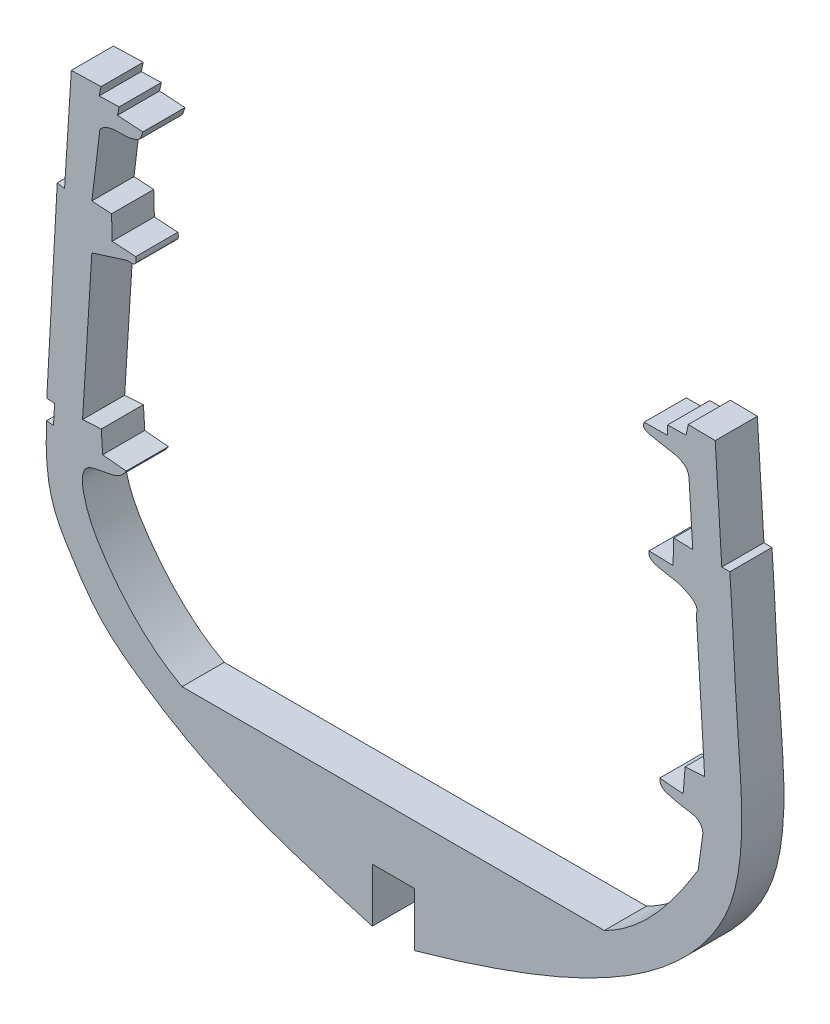
SolidWorks part; units mm, degrees
ref_plane "前视基准面" through (0, 0, 0) normal (0, 0, 1) x (1, 0, 0)
ref_plane "上视基准面" through (0, 0, 0) normal (0, 1, 0) x (1, 0, 0)
ref_plane "右视基准面" through (0, 0, 0) normal (1, 0, 0) x (0, 0, -1)
other "Configuration Table"
sketch "草图1" plane through (0, 0, 0) normal (0, 0, 1) x (1, 0, 0)
  line L0 (376.5, 617) -> (1882.5, 617) construction
  line L1 (1124.0285, 520.4301) -> (1204.1749, 520.4301)
  line L2 (1160.129, 499.1136) -> (1160.1399, 509.3173)
  line L3 (1160.1399, 509.3173) -> (1168.1384, 509.3088)
  line L4 (1168.1384, 509.3088) -> (1168.1276, 499.1038)
  line L5 (1226.4545, 591.2984) -> (1227.9811, 591.2849)
  line L6 (1226.4545, 591.2984) -> (1225.2091, 611.4627)
  line L7 (1225.2091, 611.4627) -> (1220.0951, 611.5446)
  line L8 (1220.0951, 611.5446) -> (1219.6755, 609.5706)
  line L9 (1219.6755, 609.5706) -> (1216.1736, 609.5215)
  line L10 (1216.1736, 609.5215) -> (1216.1977, 607.8038)
  line L11 (1216.1977, 607.8038) -> (1211.7165, 607.7409)
  line L12 (1220.9488, 591.4193) -> (1217.3165, 591.5037)
  line L13 (1217.3165, 591.5037) -> (1217.2104, 586.9372)
  line L14 (1217.2104, 586.9372) -> (1212.6366, 587.0434)
  line L15 (1223.2023, 555.2318) -> (1221.6271, 581.171)
  line L16 (1223.2023, 555.2318) -> (1219.5053, 555.0073)
  line L17 (1219.5053, 555.0073) -> (1219.1154, 550.3671)
  line L18 (1219.1154, 550.3671) -> (1214.6826, 550.7396)
  line L19 (1222.8747, 545.7263) -> (1221.9639, 539.2014)
  line L20 (1100.348, 591.4107) -> (1098.3587, 554.9836)
  line L21 (1098.3587, 554.9836) -> (1099.8419, 554.9026)
  line L22 (1099.8419, 554.9026) -> (1099.636, 551.1324)
  line L23 (1099.636, 551.1324) -> (1098.3117, 551.2937)
  line L24 (1100.348, 591.4107) -> (1101.7281, 591.1174)
  line L25 (1101.7281, 591.1174) -> (1103.0103, 611.2112)
  line L26 (1103.0103, 611.2112) -> (1108.6616, 611.3629)
  line L27 (1108.6616, 611.3629) -> (1108.2974, 609.6492)
  line L28 (1108.2974, 609.6492) -> (1112.0958, 609.7512)
  line L29 (1112.0958, 609.7512) -> (1111.7649, 608.1944)
  line L30 (1111.7649, 608.1944) -> (1116.5904, 607.8865)
  line L31 (1108.4423, 604.2513) -> (1106.9123, 591.6957)
  line L32 (1106.9123, 591.6957) -> (1110.6527, 591.457)
  line L33 (1110.6527, 591.457) -> (1110.7723, 587.0043)
  line L34 (1110.7723, 587.0043) -> (1115.2398, 586.7192)
  line L35 (1105.1443, 554.8802) -> (1106.9118, 583.1633)
  line L36 (1105.1443, 554.8802) -> (1108.6959, 555.1071)
  line L37 (1108.6959, 555.1071) -> (1108.958, 551.0035)
  line L38 (1108.958, 551.0035) -> (1113.4345, 550.573)
  spline S0 degree 3 poles (1098.3117, 551.2937) (1098.1627, 546.8767) (1098.1301, 539.4723) (1103.4299, 530.6686) (1108.6547, 522.9528) (1117.544, 516.5131) (1133.9474, 506.6541) (1149.1533, 502.2974) (1160.129, 499.1136) knots 0 0 0 0 0.15465 0.237651 0.346708 0.470354 0.607132 1 1 1 1
  spline S1 degree 1 poles (1168.1276, 499.1038) (1176.4134, 501.5416) knots 0 0 1 1
  spline S2 degree 3 poles (1176.4134, 501.5416) (1185.512, 504.4307) (1199.8218, 509.4916) (1217.8659, 520.9329) (1227.246, 532.267) (1231.0593, 548.101) (1229.1363, 566.6826) (1228.5999, 582.7214) (1227.9811, 591.2849) knots 0 0 0 0 0.241209 0.378188 0.536811 0.593324 0.784372 1 1 1 1
  spline S3 degree 1 poles (1220.9488, 591.4193) (1220.2509, 602.5712) knots 0 0 1 1
  spline S4 degree 3 poles (1211.7165, 607.7409) (1211.1879, 606.4018) (1213.0048, 606.2649) (1215.1963, 605.7262) (1217.9527, 605.5332) (1220.2259, 604.311) (1220.2509, 602.5712) knots 0 0 0 0 0.266116 0.349469 0.634146 1 1 1 1
  spline S5 degree 3 poles (1212.6366, 587.0434) (1212.4547, 585.7962) (1213.8901, 585.3788) (1216.2214, 584.8798) (1218.2552, 584.6955) (1220.6599, 583.4697) (1222.1127, 582.5096) (1221.6271, 581.171) knots 0 0 0 0 0.239209 0.312947 0.612237 0.73275 1 1 1 1
  spline S6 degree 3 poles (1214.6826, 550.7396) (1214.6713, 549.2701) (1216.7039, 548.7269) (1219.9461, 547.9525) (1222.6525, 547.9416) (1222.8747, 545.7263) knots 0 0 0 0 0.316887 0.545828 1 1 1 1
  spline S7 degree 3 poles (1204.1749, 520.4301) (1212.0857, 524.3632) (1217.4236, 531.9254) (1221.9639, 539.2014) knots 0 0 0 0 1 1 1 1
  spline S8 degree 1 poles (1116.5904, 607.8865) (1116.1179, 606.5072) knots 0 0 1 1
  spline S9 degree 3 poles (1116.1179, 606.5072) (1113.7911, 604.5714) (1110.6125, 606.6489) (1108.4423, 604.2513) knots 0 0 0 0 1 1 1 1
  spline S10 degree 2 poles (1115.2398, 586.7192) (1115.7012, 584.8942) (1113.7038, 585.3063) knots 0 0 0 1 1 1
  spline S11 degree 1 poles (1113.7038, 585.3063) (1106.9118, 583.1633) knots 0 0 1 1
  spline S12 degree 3 poles (1124.0285, 520.4301) (1117.7385, 523.7483) (1110.7159, 531.4213) (1105.597, 540.588) (1104.4615, 547.1625) (1109.3384, 548.5246) (1112.2766, 548.4348) (1113.4345, 550.573) knots 0 0 0 0 0.510506 0.664273 0.808402 0.847338 1 1 1 1
  dimension "D1" = 7.9985
  dimension "D2" = 10.205
extrude "凸台-拉伸1" add sketch "草图1" along normal blind 8
